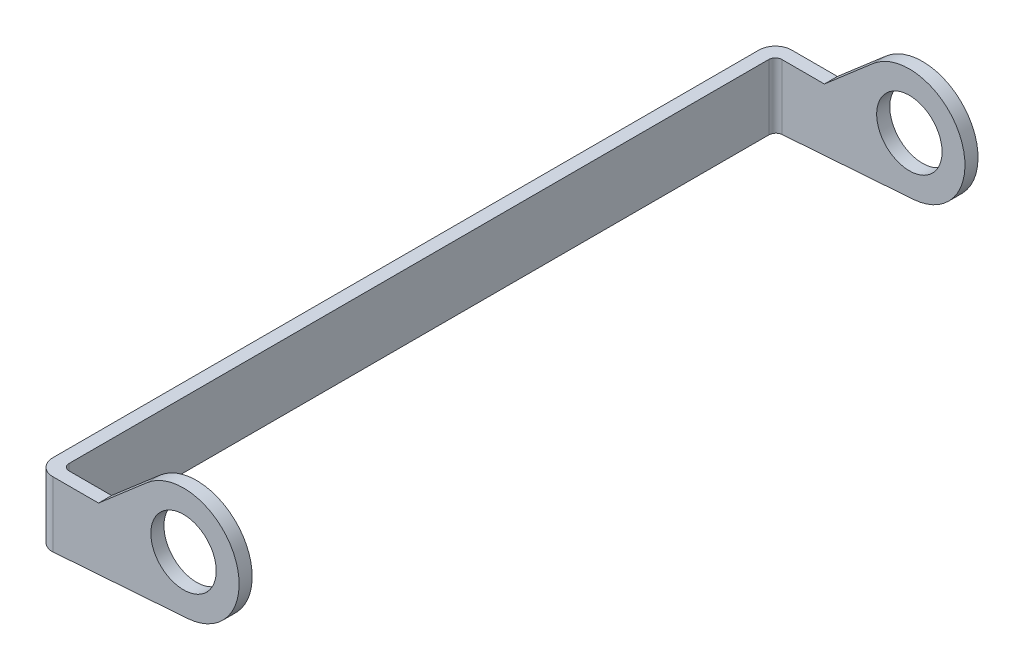
SolidWorks part; units mm, degrees
material "C40 or 38NiCrMo4"
ref_plane "Piano frontale" through (0, 0, 0) normal (0, 0, 1) x (1, 0, 0)
ref_plane "Piano superiore" through (0, 0, 0) normal (0, 1, 0) x (1, 0, 0)
ref_plane "Piano destro" through (0, 0, 0) normal (1, 0, 0) x (0, 0, -1)
sketch "Schizzo1" plane through (0, 0, 0) normal (0, 0, 1) x (1, 0, 0)
  line L0 (-1000, 0) -> (49000, 0) construction
  line L1 (0, -1000) -> (0, 49000) construction
  line L2 (-26, 0) -> (-26, 73.6219) construction
  line L3 (-26, 0) -> (-11.1154, 12.8627)
  line L5 (-41, -20) -> (1.2224, -16.956)
  line L6 (-26, 0) -> (-45, 0)
  line L7 (-45, 0) -> (-45, -20)
  line L8 (-45, -20) -> (-41, -20)
  circle A0 centre (0, 0) radius 10
  arc A1 (1.2224, -16.956) -> (-11.1154, 12.8627) centre (0, 0) ccw
  dimension "D1" = 34
  dimension "D2" = 20
  dimension "D3" = 26
  dimension "D4" = 4
  dimension "D5" = 45
  dimension "D6" = 20
extrude "Estrusione1" add sketch "Schizzo1" along normal blind 4
sketch "Schizzo2" plane through (0, 0, 4) normal (0, 0, 1) x (1, 0, 0)
  line L1 (-45, 0) -> (-41, 0)
  line L2 (-45, 0) -> (-45, -20)
  line L3 (-45, -20) -> (-41, -20)
  line L4 (-41, 0) -> (-41, -20)
extrude "Estrusione2" add sketch "Schizzo2" against normal blind 226
pattern_linear "Ripetizione a L1" count 2 spacing 222 along (0, 0, -1) of "Estrusione1"
fillet "Raccordo1" radius 5 2 edges at (-45, -10, -222) (-45, -10, 4)
fillet "Raccordo2" radius 2 2 edges at (-41, -10, -218) (-41, -10, 0)
ref_plane "Piano1" through (0, 0, -109) normal (0, 0, 1) x (1, 0, 0)
